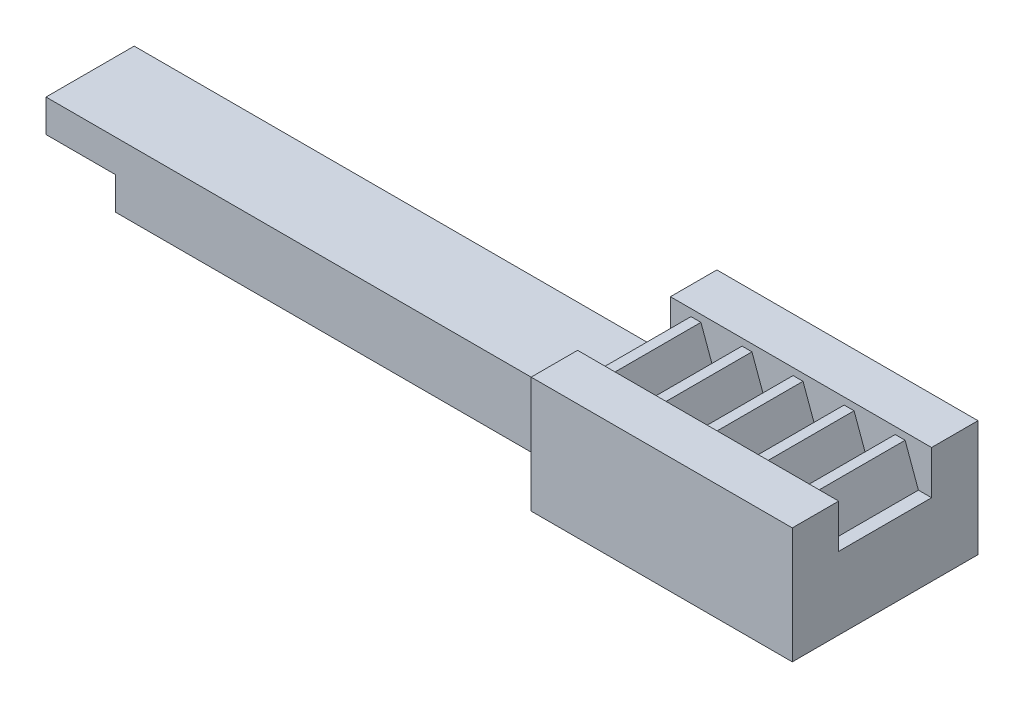
SolidWorks part; units mm, degrees
extrude "Blank" add sketch "BlankSke" against normal blind 8
sketch "BlankSke" plane through (0, 0, 0) normal (0, 0, 1) x (1, 0, 0)
  line L1 (0, 0) -> (12, 0)
  line L2 (0, 0) -> (0, 4.7)
  line L3 (0, 4.7) -> (12, 4.7)
  line L4 (12, 0) -> (12, 4.7)
  dimension "Length" = 12
  dimension "Blank_height" = 4.7
ref_plane "Plane1" through (0, 0, 0) normal (0, 0, 1) x (1, 0, 0)
ref_plane "Plane2" through (0, 0, 0) normal (0, 1, 0) x (1, 0, 0)
ref_plane "Plane3" through (0, 0, 0) normal (1, 0, 0) x (0, 0, -1)
other "Configuration Table"
sketch "HoldingSke" plane through (0, 0, 0) normal (0, 1, 0) x (1, 0, 0)
  line L0 (0, 0) -> (0.1988, 1.4147)
  line L1 (-15, 0) -> (100, 0) construction
  line L2 (0, 0) -> (-2.1039, 2.3779)
  line L3 (0, 0) -> (-11.863, 4.5341)
  line L4 (0, 0) -> (8.5716, 1.0524)
  line L5 (0, 0) -> (-23.7986, -8.8762)
  line L6 (0, 0) -> (-10.5278, -7.1032)
  line L9 (-71.009, 38.7566) -> (-59.7327, 42.8609)
  line L10 (-76.2, 3.0779) -> (-72.2, 3.0779)
  line L11 (0, 0) -> (-8, 0)
  line L12 (-76.2, 101.6) -> (-76.173, 101.6)
  line L13 (24.9733, 27.94) -> (52.9518, 28.4284)
  line L14 (24.9733, 27.94) -> (24.9743, 27.94)
  line L15 (24.9733, 27.94) -> (100.4006, 29.5858)
  circle A0 centre (0, 0) radius 19.05
  circle A1 centre (0, 0) radius 2
  circle A2 centre (0, 0) radius 12.7
  dimension "MPH" = 4
  dimension "Diameter" = 38.1
  dimension "Num_teeth" = 7
  dimension "Pitch" = 1.4286
  dimension "Show_teeth" = 998
  dimension "Thickness" = 12.7
  dimension "Ap" = 20
  dimension "Pitch_height" = 4
  dimension "Width" = 8
  dimension "Backlash" = 0.027
  dimension "Addendum_fac" = 1
  dimension "Dedendum_fac" = 1.25
  dimension "Clearance_fac" = 0.25
  dimension "Dedendum_add" = 0.001
  dimension "Length" = 12
  dimension "Module" = 0.7
sketch "TooCutSkeIll" plane through (0, 0, 0) normal (0, 0, 1) x (1, 0, 0)
  line L0 (-0.8789, 4.6816) -> (-0.3545, 3.2408)
  line L1 (-0.1891, 3.125) -> (0.1891, 3.125)
  line L2 (0.3545, 3.2408) -> (0.8789, 4.6816)
  line L3 (12, 4.7) -> (0, 4.7) construction
  line L4 (0, 0) -> (0, 64.897) construction
  line L5 (-13.208, 4) -> (12.954, 4) construction
  line L6 (0, 0) -> (12, 0) construction
  line L7 (0.6308, 4) -> (0.6308, 48.7463) construction
  line L8 (-0.6308, 4) -> (-0.6308, 48.7463) construction
  line L9 (0.9052, 4.7) -> (0.9052, 4.7254)
  line L10 (-0.9052, 4.7) -> (-0.9052, 4.7254)
  line L11 (-0.9052, 4.7254) -> (0.9052, 4.7254)
  arc A0 (0.1891, 3.125) -> (0.3545, 3.2408) centre (0.1891, 3.301) ccw
  arc A1 (-0.3545, 3.2408) -> (-0.1891, 3.125) centre (-0.1891, 3.301) ccw
  arc A2 (0.9052, 4.7) -> (0.8789, 4.6816) centre (0.9052, 4.672) ccw
  arc A3 (-0.8789, 4.6816) -> (-0.9052, 4.7) centre (-0.9052, 4.672) ccw
  dimension "Pitch_height" = 4
  dimension "Addendum_plus" = 0.7254
  dimension "Pressure_angle" = 20
  dimension "Gap_width" = 1.2616
  dimension "Dedendum" = 0.875
extrude "ToothCutIll" [suppressed] cut sketch "TooCutSkeIll" against normal through all
sketch "TooCutSkeSim" plane through (0, 0, 0) normal (0, 0, 1) x (1, 0, 0)
  line L0 (0.3123, 3.125) -> (-0.3123, 3.125)
  line L1 (0.8948, 4.7254) -> (0.3123, 3.125)
  line L2 (0, 17.4625) -> (0, 53.467) construction
  line L3 (0.8948, 4.7254) -> (-0.8948, 4.7254)
  line L6 (-0.8948, 4.7254) -> (-0.3123, 3.125)
  line L9 (-0.6308, 4) -> (0.6308, 4) construction
  line L10 (0, 0) -> (12, 0) construction
  line L11 (0.6308, 4) -> (0.6308, 53.467) construction
  line L12 (-0.6308, 4) -> (-0.6308, 53.467) construction
  dimension "Pitch_height" = 4
  dimension "Addendum_plus" = 0.7254
  dimension "Pressure_angle" = 20
  dimension "Gap_width" = 1.2616
  dimension "Dedendum" = 0.875
extrude "ToothCutSim" cut sketch "TooCutSkeSim" against normal through all
pattern_linear "TeethCuts" count 6 spacing 2.1991 along (1, 0, 0) of "ToothCutIll", "ToothCutSim"
sketch "Sketch1" plane through (0, 0, 0) normal (0, -1, 0) x (1, 0, 0)
  line L0 (0, -2) -> (12, -2)
  line L1 (0, 0) -> (12, 0)
  line L2 (0, 0) -> (0, -2)
  line L3 (0, -8) -> (12, -8)
  line L4 (12, 0) -> (12, -2)
  line L5 (0, -6) -> (0, -8)
  line L6 (0, -6) -> (12, -6)
  line L7 (12, -6) -> (12, -8)
  dimension "D1" = 2
  dimension "D2" = 2
extrude "Boss-Extrude1" add sketch "Sketch1" against normal blind 5
sketch "Sketch2" plane through (0, 0, 0) normal (0, 1, 0) x (1, 0, 0)
  line L0 (0, 8) -> (12, 8) construction
  line L1 (12, 0) -> (11.25, 0)
  line L2 (12, 0) -> (12, 8)
  line L3 (12, 8) -> (11.25, 8)
  line L4 (11.25, 0) -> (11.25, 8)
  dimension "D1" = 0.75
extrude "Cut-Extrude1" cut sketch "Sketch2" along normal blind 5
sketch "Sketch3" plane through (0, 0, 0) normal (1, 0, 0) x (0, 0, -1)
  line L0 (8, 0) -> (0, 0) construction
  line L1 (2.1, 0.1) -> (5.9, 0.1)
  line L2 (2.1, 0.1) -> (2.1, 2.9)
  line L3 (2.1, 2.9) -> (5.9, 2.9)
  line L4 (5.9, 0.1) -> (5.9, 2.9)
  line L6 (6, 3.125) -> (2, 3.125) construction
  line L7 (4, 2.9) -> (4, 3.125) construction
  dimension "D1" = 2.8
  dimension "D2" = 0.1
  dimension "3.8" = 3.8
extrude "Boss-Extrude2" add sketch "Sketch3" against normal blind 23
sketch "Sketch4" plane through (-23, 0, 0) normal (-1, 0, 0) x (0, 0, 1)
  line L0 (-5.9, 1.5) -> (-2.1, 1.5)
  line L1 (-5.9, 0.1) -> (-5.9, 2.9) construction
  line L2 (-2.1, 2.9) -> (-2.1, 0.1) construction
  line L3 (-2.1, 1.5) -> (-2.1, 0.1)
  line L4 (-2.1, 0.1) -> (-5.9, 0.1)
  line L5 (-5.9, 0.1) -> (-5.9, 1.5)
extrude "Cut-Extrude2" cut sketch "Sketch4" against normal blind 3
equation "' \"Module@HoldingSke\" = 6.35"
equation "' \"Num_teeth@HoldingSke\" = 12"
equation "' \"Ap@HoldingSke\" =  20"
equation "' \"Ap@HoldingSke\" = 20"
equation "' \"Width@HoldingSke\" = 0.25 * 25.4"
equation "' \"Show_teeth@HoldingSke\" = 500"
equation "' \"Backlash@HoldingSke\" = 0.009 * 25.4"
equation "' \"Addendum_fac@HoldingSke\" = 1.0"
equation "' \"Dedendum_fac@HoldingSke\" = 1.25"
equation "' \"Dedendum_add@HoldingSke\" = 0.00005 * 25.4"
equation "' \"Clearance_fac@HoldingSke\" = 0.25"
equation "' \"Pitch_height@HoldingSke\" = 1 * 25.4"
equation "' \"Length@HoldingSke\" = 4.71 * 25.4"
equation "\"Pitch@HoldingSke\" = 1 / \"Module@HoldingSke\""
equation "\"MPH@HoldingSke\" = \"Dedendum_fac@HoldingSke\" / \"Pitch@HoldingSke\" + 2 * \"Dedendum_add@HoldingSke\" + 0.002 * 25.4"
equation "\"MPH@HoldingSke\" = ((sgn( \"MPH@HoldingSke\" - \"Pitch_height@HoldingSke\")+1)*( \"MPH@HoldingSke\" - \"Pitch_height@HoldingSke\"))/2 + \"Pitch_height@HoldingSke\""
equation "\"Blank_height@BlankSke\" = \"Pitch_height@HoldingSke\" + \"Addendum_fac@HoldingSke\"  / \"Pitch@HoldingSke\" "
equation "\"Length@BlankSke\" =  \"Length@HoldingSke\""
equation "\"Face_width@Blank\" = \"Width@HoldingSke\""
equation "\"Pressure_angle@TooCutSkeIll\" = \"Ap@HoldingSke\""
equation "\"Addendum_plus@TooCutSkeIll\" =  \"Addendum_fac@HoldingSke\"  / \"Pitch@HoldingSke\" + 0.001 *25.4"
equation "\"Dedendum@TooCutSkeIll\" = \"Dedendum_fac@HoldingSke\"  / \"Pitch@HoldingSke\""
equation "\"Pitch_height@TooCutSkeIll\" =  \"MPH@HoldingSke\""
equation "\"Gap_width@TooCutSkeIll\" = 3.14159265 / 2 / \"Pitch@HoldingSke\" + 6 * \"Backlash@HoldingSke\""
equation "\"Pressure_angle@TooCutSkeSim\" = \"Ap@HoldingSke\""
equation "\"Addendum_plus@TooCutSkeSim\" =  \"Addendum_fac@HoldingSke\"  / \"Pitch@HoldingSke\" + 0.001 * 25.4"
equation "\"Dedendum@TooCutSkeSim\" = \"Dedendum_fac@HoldingSke\"  / \"Pitch@HoldingSke\""
equation "\"Pitch_height@TooCutSkeSim\" =  \"MPH@HoldingSke\""
equation "\"Gap_width@TooCutSkeSim\" = 3.14159265 / 2 / \"Pitch@HoldingSke\" + 6 * \"Backlash@HoldingSke\""
equation "\"Root_fillet@TooCutSkeIll\" = \"Clearance_fac@HoldingSke\" / \"Pitch@HoldingSke\" + \"Dedendum_add@HoldingSke\""
equation "\"Break_rad@TooCutSkeIll\" = 0.02 / \"Pitch@HoldingSke\" * 2"
equation "\"Linear_pitch@TeethCuts\" = 3.14159265 / \"Pitch@HoldingSke\""
equation "\"Num_teeth@HoldingSke\" = int( ( \"Length@HoldingSke\" + 0 ) / (3.14159265 / \"Pitch@HoldingSke\")) + 0.9999  + 1"
equation " \"Num_teeth@TeethCuts\" = int( \"Show_teeth@HoldingSke\" ) + 1"
equation " \"Num_teeth@TeethCuts\" = ((sgn( \"Num_teeth@TeethCuts\" - \"Num_teeth@HoldingSke\" )-1)*( \"Num_teeth@TeethCuts\" - \"Num_teeth@HoldingSke\" ))/-2+ \"Num_teeth@HoldingSke\""
equation " \"Num_teeth@TeethCuts\" = ((sgn( \"Num_teeth@TeethCuts\" - 2.0)+1)*( \"Num_teeth@TeethCuts\" - 2.0))/2 +2.0"
